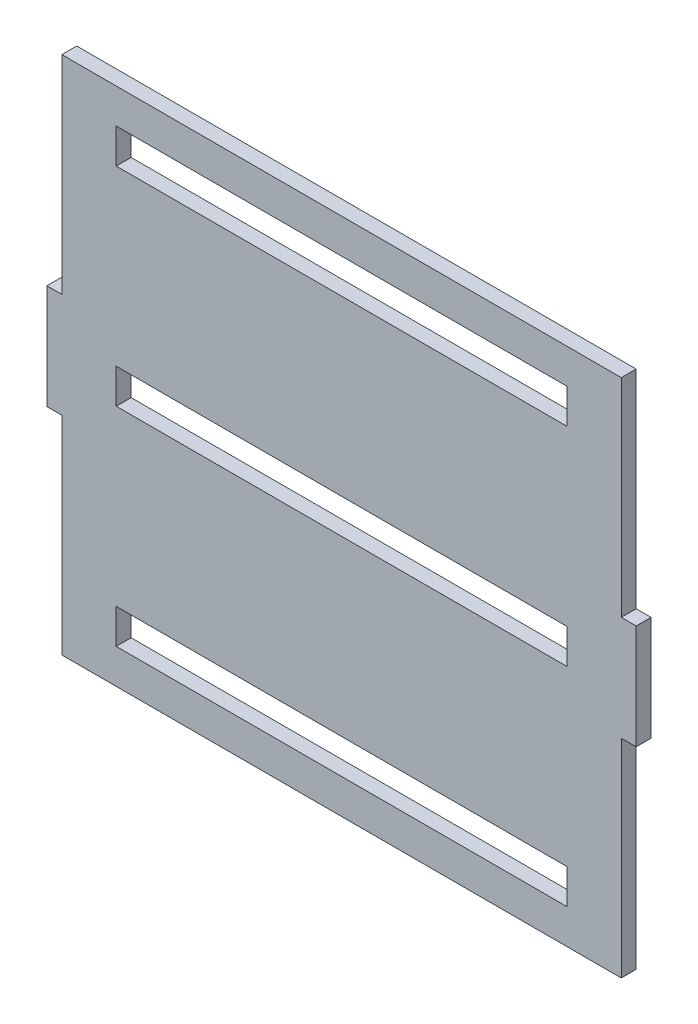
SolidWorks part; units mm, degrees
ref_plane "Front Plane" through (0, 0, 0) normal (0, 0, 1) x (1, 0, 0)
ref_plane "Top Plane" through (0, 0, 0) normal (0, 1, 0) x (1, 0, 0)
ref_plane "Right Plane" through (0, 0, 0) normal (1, 0, 0) x (0, 0, -1)
sketch "Sketch1" plane through (0, 0, 0) normal (0, 0, 1) x (1, 0, 0)
  line L0 (80.7, 15.1) -> (80.7, 75)
  line L1 (-80.7, -75) -> (80.7, -75)
  line L2 (-80.7, -75) -> (-80.7, -15.1)
  line L3 (-80.7, 75) -> (80.7, 75)
  line L4 (80.7, -75) -> (80.7, -15.1)
  line L5 (-80.7, -75) -> (80.7, 75) construction
  line L6 (-80.7, 75) -> (80.7, -75) construction
  line L7 (-80.7, 15.1) -> (-85, 15.1)
  line L9 (-80.7, -15.1) -> (-85, -15.1)
  line L10 (-85, 15.1) -> (-85, -15.1)
  line L11 (80.7, 15.1) -> (85, 15.1)
  line L13 (80.7, -15.1) -> (85, -15.1)
  line L14 (85, 15.1) -> (85, -15.1)
  line L15 (-80.7, 15.1) -> (-80.7, 75)
  line L17 (-65, 65) -> (65, 65)
  line L18 (-65, 65) -> (-65, 55)
  line L19 (-65, 55) -> (65, 55)
  line L20 (65, 65) -> (65, 55)
  line L21 (-65, -5) -> (65, -5)
  line L22 (-65, -5) -> (-65, 5)
  line L23 (-65, 5) -> (65, 5)
  line L24 (65, -5) -> (65, 5)
  line L25 (-65, -65) -> (65, -65)
  line L26 (-65, -65) -> (-65, -55)
  line L27 (-65, -55) -> (65, -55)
  line L28 (65, -65) -> (65, -55)
  point P0 (0, 0)
  point P14 (85, 0)
  point P15 (-85, 0)
  point P20 (0, 65)
  point P21 (0, 75)
  point P31 (0, -5)
  point P32 (65, 0)
  point P33 (0, -55)
  dimension "D1" = 161.4
  dimension "D2" = 150
  dimension "D3" = 30.2
  dimension "D4" = 30.2
  dimension "D5" = 4.3
  dimension "D6" = 4.3
  dimension "D7" = 130
  dimension "D8" = 10
  dimension "D9" = 10
  dimension "D10" = 10
extrude "Boss-Extrude1" add sketch "Sketch1" along normal blind 4.3
